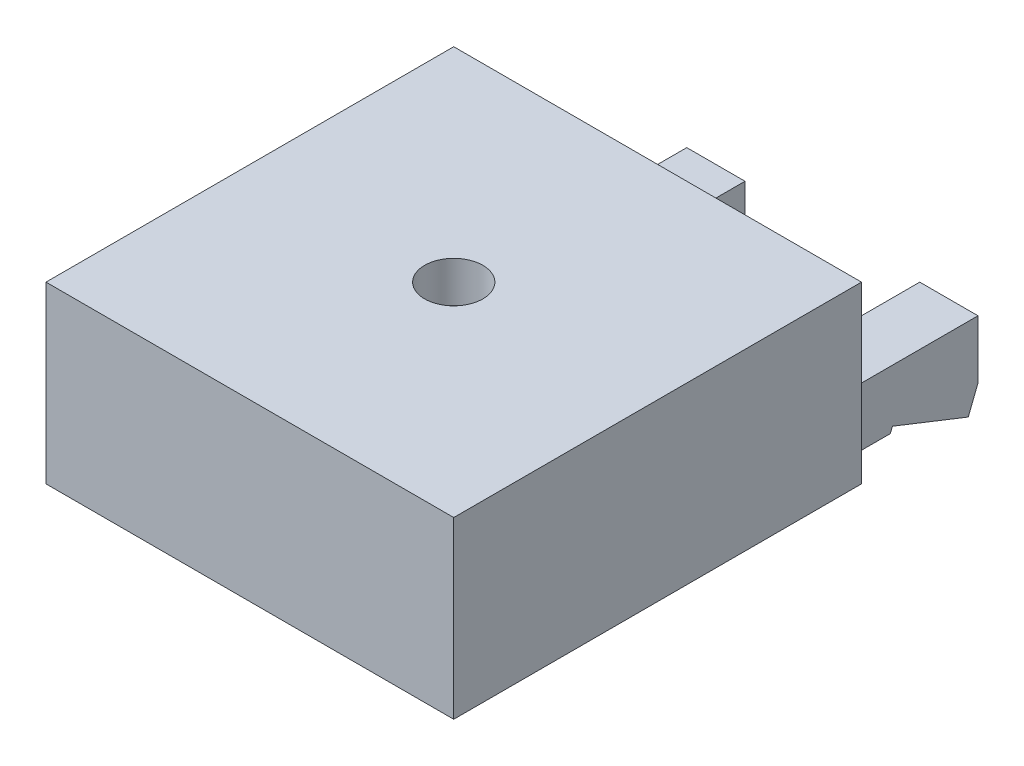
SolidWorks part; units mm, degrees
ref_plane "Plan de face" through (0, 0, 0) normal (0, 0, 1) x (1, 0, 0)
ref_plane "Plan de dessus" through (0, 0, 0) normal (0, 1, 0) x (1, 0, 0)
ref_plane "Plan de droite" through (0, 0, 0) normal (1, 0, 0) x (0, 0, -1)
sketch "Esquisse1" plane through (0, 0, 0) normal (0, 1, 0) x (1, 0, 0)
  line L1 (0, 0) -> (70, 0)
  line L2 (0, 0) -> (0, 70)
  line L3 (0, 70) -> (70, 70)
  line L4 (70, 0) -> (70, 70)
  dimension "D1" = 70
  dimension "D2" = 70
extrude "Boss.-Extru.4" add sketch "Esquisse1" along normal blind 30
sketch "Esquisse5" plane through (0, 0, 0) normal (0, -1, 0) x (-1, 0, 0)
  line L0 (-70, 0) -> (-70, 70) construction
  line L1 (-5, 5) -> (-65, 5)
  line L2 (-5, 5) -> (-5, 65)
  line L3 (-5, 65) -> (-65, 65)
  line L4 (-65, 5) -> (-65, 65)
  line L5 (0, 70) -> (0, 0) construction
  line L6 (0, 0) -> (-70, 0) construction
  line L7 (-70, 70) -> (0, 70) construction
  dimension "D1" = 5
  dimension "D2" = 5
  dimension "D3" = 5
  dimension "D4" = 5
extrude "Enlèv. mat.-Extru.3" cut sketch "Esquisse5" against normal blind 23
sketch "Esquisse6" plane through (0, 23, 0) normal (0, -1, 0) x (-1, 0, 0)
  line L0 (0, 0) -> (-70, 0) construction
  line L1 (0, 70) -> (0, 0) construction
  circle A0 centre (-35, 35) radius 5
  dimension "D1" = 10
  dimension "D2" = 35
  dimension "D3" = 35
extrude "Enlèv. mat.-Extru.4" cut sketch "Esquisse6" against normal blind 23 contours A0
sketch "Esquisse24" plane through (0, 0, -70) normal (0, 0, -1) x (-1, 0, 0)
  line L0 (0, 30) -> (-10.005, 30)
  line L1 (-70, 30) -> (0, 30) construction
  line L2 (-20.005, 30) -> (-50.005, 30)
  line L3 (-50.005, 30) -> (-60.005, 30)
  line L4 (-60.005, 30) -> (-60.005, 0)
  line L5 (-70, 0) -> (0, 0) construction
  line L10 (-60.005, 0) -> (-50.005, 0)
  line L11 (-50.005, 0) -> (-20.005, 0)
  line L12 (-20.005, 0) -> (-10.005, 0)
  dimension "D1" = 10
  dimension "D2" = 10.005
  dimension "D3" = 10
  dimension "D4" = 30
sketch "Esquisse28" plane through (0, 0, 0) normal (0, -1, 0) x (1, 0, 0)
  line L0 (50.005, -70) -> (60.005, -70) construction
  line L1 (50.005, -70) -> (60.005, -70)
  line L2 (50.005, -70) -> (50.005, -100)
  line L3 (50.005, -100) -> (60.005, -100)
  line L4 (60.005, -70) -> (60.005, -100)
  dimension "D1" = 30
extrude "Boss.-Extru.8" add sketch "Esquisse28" along normal mid plane 10
sketch "Esquisse29" plane through (60.005, 0, 0) normal (1, 0, 0) x (0, 0, -1)
  line L0 (70, -5) -> (85, -5)
  line L1 (100, -5) -> (97.2832, -11.8754)
  line L2 (100, -5) -> (70, -5) construction
  line L3 (97.2832, -11.8754) -> (98.6416, -8.4377)
  line L4 (98.6416, -8.4377) -> (97.9624, -10.1566)
  line L5 (97.9624, -10.1566) -> (85, -5)
  line M5 (70, -5) -> (100, -5)
extrude "Boss.-Extru.9" add sketch "Esquisse29" against normal blind 10 contours L5 L1 M5
sketch "Esquisse30" plane through (0, 0, 0) normal (0, -1, 0) x (1, 0, 0)
  line L0 (0, -70) -> (10.005, -70) construction
  line L1 (10.005, -70) -> (20.005, -70)
  line L2 (10.005, -70) -> (10.005, -100)
  line L3 (10.005, -100) -> (20.005, -100)
  line L4 (20.005, -70) -> (20.005, -100)
  dimension "D1" = 30
extrude "Boss.-Extru.10" add sketch "Esquisse30" along normal mid plane 10
sketch "Esquisse39" plane through (10.005, 0, 0) normal (-1, 0, 0) x (0, 0, 1)
  line L0 (-100, -5) -> (-95.9609, -15.2316)
  line L1 (-95.9609, -15.2316) -> (-85, -5)
  line L2 (-70, -5) -> (-100, -5) construction
  line L3 (-85, -5) -> (-100, -5)
  dimension "D1" = 11
extrude "Boss.-Extru.14" add sketch "Esquisse39" against normal blind 10
sketch "Esquisse40" plane through (0, -34.8279, -88.2251) normal (0, -0.3672, -0.9301) x (-1, 0, 0)
  line L0 (-20.005, 21.0679) -> (-20.005, 22.0679)
  line L1 (-20.005, 32.0679) -> (-20.005, 21.0679) construction
  line L2 (-20.005, 22.0679) -> (-10.005, 21.0679)
  line L3 (-10.005, 21.0679) -> (-20.005, 21.0679)
  dimension "D1" = 1
extrude "Enlèv. mat.-Extru.6" cut sketch "Esquisse40" against normal blind 10
sketch "Esquisse41" plane through (0, -34.8529, -88.2039) normal (0, -0.3675, -0.93) x (-1, 0, 0)
  line L4 (-60.005, 27.5545) -> (-60.005, 26.5545)
  line L5 (-60.005, 32.099) -> (-60.005, 26.5545) construction
  line L6 (-60.005, 26.5545) -> (-50.005, 26.5545)
  line L7 (-50.005, 26.5545) -> (-60.005, 27.5545)
  dimension "D1" = 1
extrude "Enlèv. mat.-Extru.15" cut sketch "Esquisse41" against normal blind 14
